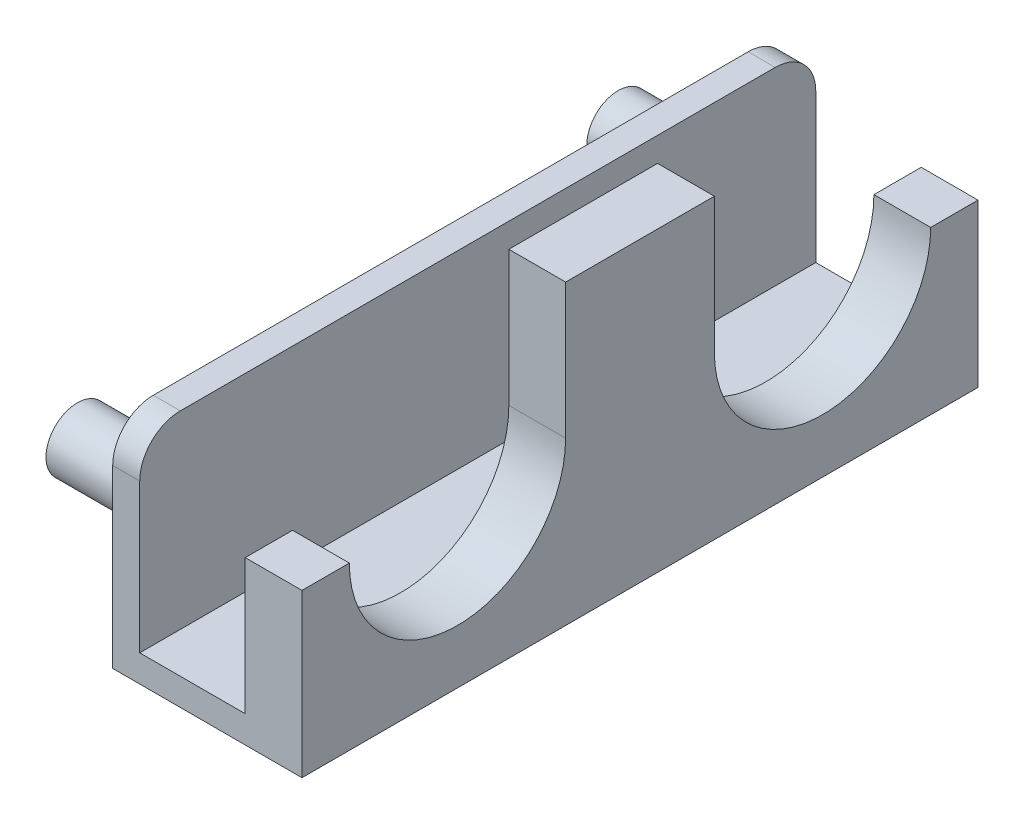
SolidWorks part; units mm, degrees
ref_plane "Front Plane" through (0, 0, 0) normal (0, 0, 1) x (1, 0, 0)
ref_plane "Top Plane" through (0, 0, 0) normal (0, 1, 0) x (1, 0, 0)
ref_plane "Right Plane" through (0, 0, 0) normal (1, 0, 0) x (0, 0, -1)
sketch "Sketch1" plane through (0, 0, 0) normal (1, 0, 0) x (0, 0, -1)
  line L2 (112.542, 29.7792) -> (62.542, 29.7792)
  line L3 (112.542, 29.7792) -> (112.542, 13.7792)
  line L4 (112.542, 13.7792) -> (62.542, 13.7792)
  line L5 (62.542, 29.7792) -> (62.542, 13.7792)
  dimension "D1" = 50
  dimension "D2" = 16
extrude "Boss-Extrude1" add sketch "Sketch1" along normal blind 2
sketch "Sketch2" plane through (0, 0, 0) normal (-1, 0, 0) x (0, 0, 1)
  circle A0 centre (-107.9334, 21.7792) radius 2.325
  circle A5 centre (-67.9334, 21.7792) radius 2.325
  circle A6 centre (-99.9334, 21.7792) radius 2.325 [skipped]
  circle A7 centre (-91.9334, 21.7792) radius 2.325 [skipped]
  circle A8 centre (-83.9334, 21.7792) radius 2.325 [skipped]
  circle A9 centre (-75.9334, 21.7792) radius 2.325 [skipped]
  dimension "D1" = 4.65
  dimension "D2" = 6
extrude "Boss-Extrude2" add sketch "Sketch2" along normal blind 8
sketch "Sketch3" plane through (2, 0, 0) normal (1, 0, 0) x (0, 0, -1)
  line L0 (112.542, 13.7792) -> (112.542, 29.7792) construction
  line L1 (62.542, 13.7792) -> (112.542, 13.7792)
  line L2 (62.542, 13.7792) -> (62.542, 15.7792)
  line L3 (62.542, 15.7792) -> (112.542, 15.7792)
  line L4 (112.542, 13.7792) -> (112.542, 15.7792)
  dimension "D1" = 2
extrude "Boss-Extrude3" add sketch "Sketch3" along normal blind 12
sketch "Sketch4" plane through (0, 15.7792, 0) normal (0, 1, 0) x (1, 0, 0)
  line L0 (14, 62.542) -> (2, 62.542) construction
  line L1 (14, 112.542) -> (9.8, 112.542)
  line L2 (14, 112.542) -> (14, 62.542)
  line L3 (14, 62.542) -> (9.8, 62.542)
  line L4 (9.8, 112.542) -> (9.8, 62.542)
  dimension "D1" = 4.2
extrude "Boss-Extrude4" add sketch "Sketch4" along normal blind 20
sketch "Sketch7" plane through (14, 0, 0) normal (1, 0, 0) x (0, 0, -1)
  line L0 (74.042, 33.7792) -> (74.042, 35.7792) construction
  line L1 (62.542, 35.7792) -> (112.542, 35.7792) construction
  line L2 (66.042, 25.7792) -> (62.542, 25.7792) construction
  line L3 (62.542, 35.7792) -> (62.542, 13.7792) construction
  circle A0 centre (74.042, 25.7792) radius 8
  circle A1 centre (101.042, 25.7792) radius 8
  dimension "D1" = 16
  dimension "D3" = 2
  dimension "D4" = 3.5
  dimension "D2" = 2
extrude "Cut-Extrude1" cut sketch "Sketch7" against normal blind 4.2 and the other way through all
sketch "Sketch8" plane through (14, 0, 0) normal (1, 0, 0) x (0, 0, -1)
  line L0 (66.042, 25.7792) -> (66.042, 35.7792)
  line L1 (62.542, 35.7792) -> (112.542, 35.7792) construction
  line L2 (66.042, 35.7792) -> (82.042, 35.7792)
  line L3 (82.042, 35.7792) -> (82.042, 25.7792)
  line L4 (82.042, 25.7792) -> (66.042, 25.7792)
  line L5 (93.042, 25.7792) -> (93.042, 35.7792)
  line L6 (93.042, 35.7792) -> (109.042, 35.7792)
  line L7 (109.042, 35.7792) -> (109.042, 25.7792)
  line L8 (109.042, 25.7792) -> (93.042, 25.7792)
  circle A0 centre (74.042, 25.7792) radius 8 construction
  circle A1 centre (101.042, 25.7792) radius 8 construction
extrude "Cut-Extrude2" cut sketch "Sketch8" against normal blind 4.2
fillet "Fillet1" radius 3 2 edges at (1, 29.7792, -62.542) (1, 29.7792, -112.542)
sketch "Sketch9" plane through (14, 0, 0) normal (1, 0, 0) x (0, 0, -1)
  line L10 (66.042, 25.7792) -> (62.542, 25.7792)
  line L11 (66.042, 25.7792) -> (66.042, 35.7792)
  line L12 (66.042, 35.7792) -> (62.542, 35.7792)
  line L13 (62.542, 25.7792) -> (62.542, 35.7792)
  line L14 (109.042, 25.7792) -> (112.542, 25.7792)
  line L15 (109.042, 25.7792) -> (109.042, 35.7792)
  line L16 (109.042, 35.7792) -> (112.542, 35.7792)
  line L17 (112.542, 25.7792) -> (112.542, 35.7792)
extrude "Cut-Extrude4" cut sketch "Sketch9" against normal blind 10
